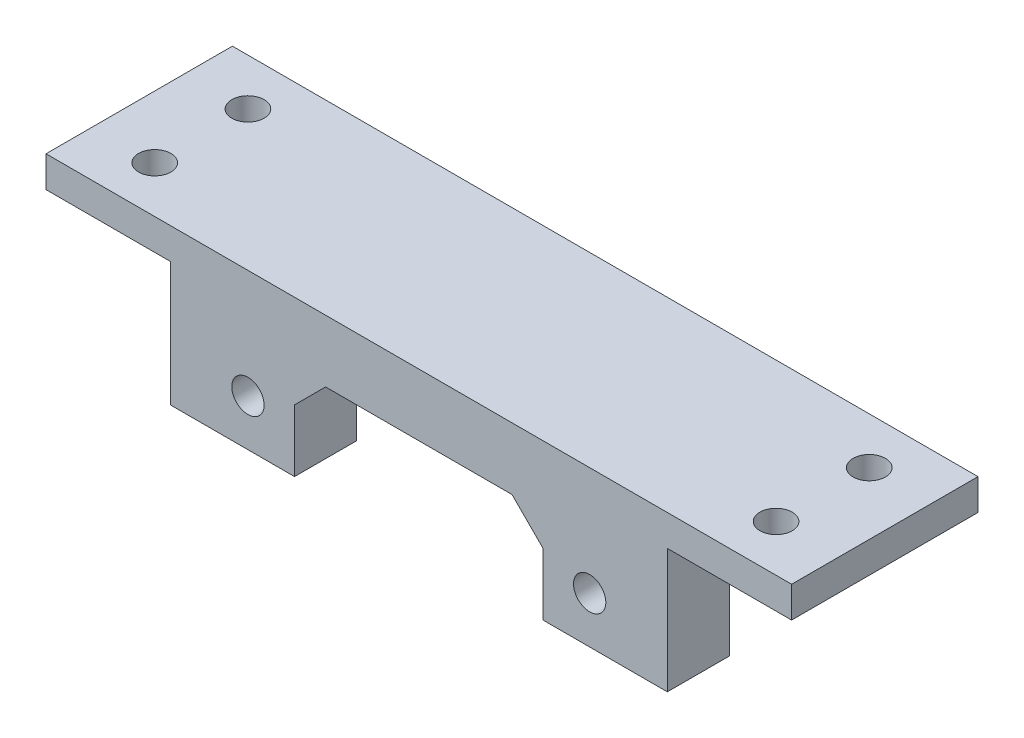
SolidWorks part; units mm, degrees
ref_plane "前视基准面" through (0, 0, 0) normal (0, 0, 1) x (1, 0, 0)
ref_plane "上视基准面" through (0, 0, 0) normal (0, 1, 0) x (1, 0, 0)
ref_plane "右视基准面" through (0, 0, 0) normal (1, 0, 0) x (0, 0, -1)
sketch "草图1" plane through (0, 0, 0) normal (0, 0, 1) x (1, 0, 0)
  line L0 (20, 0) -> (20, -20)
  line L1 (0, 0) -> (20, 0)
  line L2 (0, 0) -> (0, 5)
  line L3 (0, 5) -> (120, 5)
  line L4 (120, 0) -> (120, 5)
  line L5 (20, -20) -> (40, -20)
  line L6 (40, -20) -> (40, -5)
  line L7 (80, -5) -> (80, -20)
  line L8 (80, -20) -> (100, -20)
  line L9 (100, -20) -> (100, 0)
  line L10 (40, -5) -> (80, -5)
  line L11 (100, 0) -> (120, 0)
  dimension "D1" = 120
  dimension "D2" = 5
  dimension "D3" = 20
  dimension "D4" = 20
  dimension "D5" = 20
  dimension "D6" = 20
  dimension "D9" = 5
extrude "凸台-拉伸1" add sketch "草图1" along normal blind 30 contours L5 L6 L1 L0 | L1 L4 L3 L2 | L8 L9 L1 L7
chamfer "倒角2" distance 5 angle 45 2 edges at (80, -5, 15) (40, -5, 15)
sketch "草图2" plane through (0, 5, 0) normal (0, 1, 0) x (1, 0, 0)
  line L0 (0, -30) -> (0, 0) construction
  line L2 (0, -30) -> (120, -30) construction
  circle A0 centre (10, -7.5) radius 2.6
  circle A1 centre (10, -22.5) radius 2.6
  circle A2 centre (110, -22.5) radius 2.6
  circle A3 centre (110, -7.5) radius 2.6
  dimension "D7" = 5.2
  dimension "D8" = 5.2
  dimension "D1" = 10
  dimension "D2" = 10
  dimension "D3" = 2
  dimension "D5" = 15
  dimension "D6" = 7.5
extrude "切除-拉伸1" cut sketch "草图2" against normal through all
sketch "草图3" plane through (20, 0, 0) normal (-1, 0, 0) x (0, 0, 1)
  line L0 (10, -20) -> (10, -5)
  line L1 (30, -20) -> (0, -20) construction
  line L2 (10, -5) -> (20, -5)
  line L3 (20, -5) -> (20, -20)
  line L4 (20, -20) -> (10, -20)
  line L5 (30, 0) -> (30, -20) construction
  dimension "D1" = 10
  dimension "D2" = 15
  dimension "D3" = 10
extrude "切除-拉伸2" cut sketch "草图3" against normal through all
sketch "草图4" plane through (0, 0, 0) normal (0, 0, -1) x (-1, 0, 0)
  line L0 (-80, -10) -> (-80, -20) construction
  line L1 (-80, -20) -> (-100, -20) construction
  circle A0 centre (-87.5, -12.5) radius 2.6
  circle A1 centre (-32.5, -12.5) radius 2.6
  dimension "D1" = 5.2
  dimension "D2" = 7.5
  dimension "D3" = 7.5
  dimension "D4" = 2
extrude "切除-拉伸3" cut sketch "草图4" against normal through all
